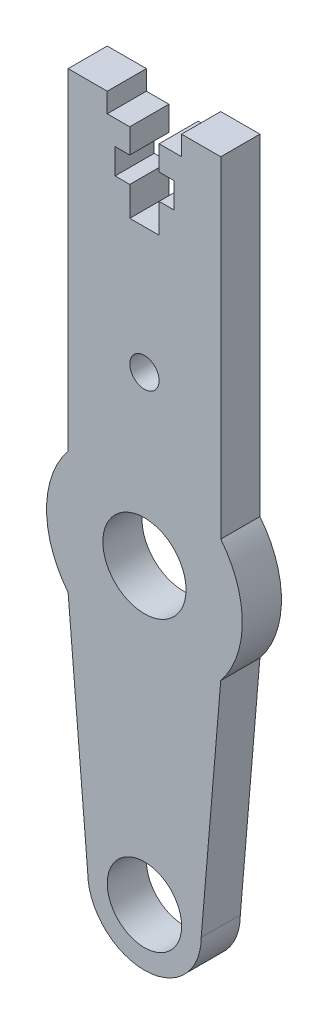
SolidWorks part; units mm, degrees
ref_plane "前视基准面" through (0, 0, 0) normal (0, 0, 1) x (1, 0, 0)
ref_plane "上视基准面" through (0, 0, 0) normal (0, 1, 0) x (1, 0, 0)
ref_plane "右视基准面" through (0, 0, 0) normal (1, 0, 0) x (0, 0, -1)
sketch "草图1" plane through (0, 0, 0) normal (0, 0, 1) x (1, 0, 0)
  line L56 (1.4972, 22.6101) -> (3.7972, 22.6101)
  line L63 (-3.8028, 24.6101) -> (-7.8028, 24.6101)
  line L66 (-3.8028, 22.6101) -> (-1.5028, 22.6101)
  line L69 (-3.8028, 24.6101) -> (-3.8028, 22.6101)
  line L70 (-3.0028, 20.1101) -> (-3.0028, 17.5101)
  line L71 (-3.0028, 17.5101) -> (-1.5028, 17.5101)
  line L72 (-1.5028, 17.5101) -> (-1.5028, 14.5101)
  line L73 (1.4972, 17.5101) -> (1.4972, 14.5101)
  line L74 (2.9972, 17.5101) -> (1.4972, 17.5101)
  line L75 (2.9972, 20.1101) -> (2.9972, 17.5101)
  line L76 (-1.5028, 20.1101) -> (-3.0028, 20.1101)
  line L77 (-1.5028, 14.5101) -> (1.4972, 14.5101)
  line L78 (1.4972, 20.1101) -> (2.9972, 20.1101)
  line L79 (-1.5028, 20.1101) -> (-1.5028, 22.6101)
  line L80 (1.4972, 20.1101) -> (1.4972, 22.6101)
  line L81 (-7.8028, 24.6101) -> (-7.8028, -9.2321)
  line L82 (3.7972, 22.6101) -> (3.7972, 24.6101)
  line L83 (3.7972, 24.6101) -> (7.7972, 24.6101)
  line L84 (-0.0028, -15.4899) -> (-0.0028, 14.5101) construction
  line L85 (7.7972, -9.2321) -> (7.7972, 24.6101)
  line L86 (-0.0028, -15.4899) -> (-0.0028, -45.4899) construction
  line L87 (-5.8028, -45.4899) -> (-7.8028, -21.7477)
  line L88 (5.7972, -45.4899) -> (7.7972, -21.7477)
  line L89 (-0.0028, -15.4899) -> (-0.0028, 1.6301) construction
  circle A8 centre (-0.0028, -15.4899) radius 4.25
  circle A9 centre (-0.0028, -15.4899) radius 10 construction
  arc A10 (7.7972, -9.2321) -> (-7.8028, -9.2321) centre (-0.0028, -15.4899) cw construction
  circle A11 centre (-0.0028, -45.4899) radius 3.8
  circle A12 centre (-0.0028, -45.4899) radius 5.8 construction
  arc A13 (-5.8028, -45.4899) -> (5.7972, -45.4899) centre (-0.0028, -45.4899) ccw
  arc A14 (-7.8028, -9.2321) -> (-7.8028, -21.7477) centre (-0.0028, -15.4899) ccw
  arc A15 (7.7972, -9.2321) -> (7.7972, -21.7477) centre (-0.0028, -15.4899) cw
  circle A16 centre (-0.0028, 1.6301) radius 1.5
extrude "凸台-拉伸1" add sketch "草图1" along normal blind 4
sketch "草图2" plane through (0, 0, 4) normal (0, 0, 1) x (1, 0, 0)
  circle A0 centre (-0.0028, -15.4899) radius 5
sketch "草图3" plane through (0, 0, 0) normal (0, 0, -1) x (-1, 0, 0)
  circle A0 centre (0.0028, -15.4899) radius 5
sketch "草图4" plane through (0, 22.6101, 0) normal (0, 1, 0) x (1, 0, 0)
  line L0 (-1.5028, -2) -> (1.4972, -2)
  line L1 (-1.5028, -4) -> (-1.5028, 0) construction
  line L2 (1.4972, -4) -> (1.4972, 0) construction
  circle A0 centre (-0.0028, -2) radius 1.5
sketch "草图5" plane through (0, 0, 4) normal (0, 0, 1) x (1, 0, 0)
  circle A0 centre (-0.0028, 1.6301) radius 1.5
